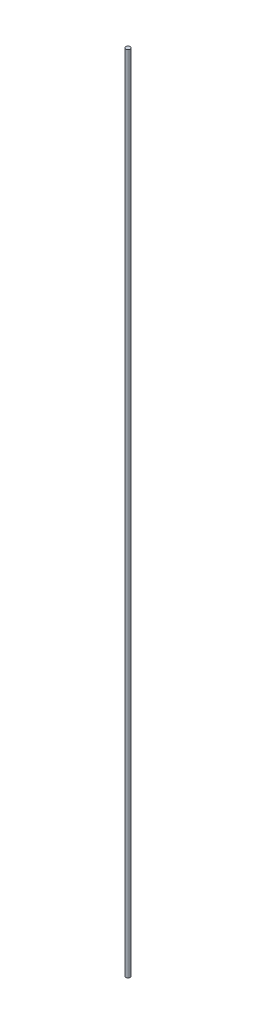
SolidWorks part; units mm, degrees
material "Custom Plastic"
ref_plane "Front Plane" through (0, 0, 0) normal (0, 0, 1) x (1, 0, 0)
ref_plane "Top Plane" through (0, 0, 0) normal (0, 1, 0) x (1, 0, 0)
ref_plane "Right Plane" through (0, 0, 0) normal (1, 0, 0) x (0, 0, -1)
sketch "Sketch1" plane through (0, 0, 0) normal (0, 1, 0) x (1, 0, 0)
  circle A0 centre (0, 0) radius 2
  dimension "D1" = 4
extrude "Boss-Extrude2" add sketch "Sketch1" along normal blind 700
cosmetic thread "Cosmetic Thread4" parameters "D2"=3.22
